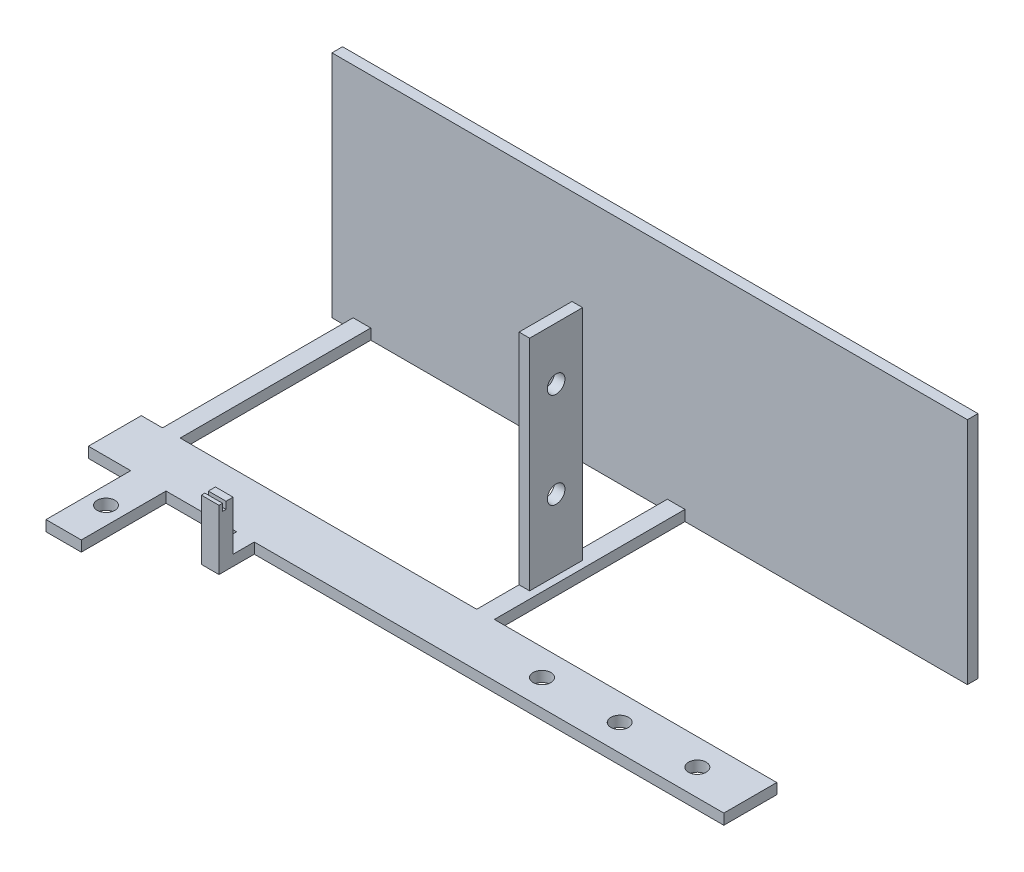
SolidWorks part; units mm, degrees
ref_plane "Front Plane" through (0, 0, 0) normal (0, 0, 1) x (1, 0, 0)
ref_plane "Top Plane" through (0, 0, 0) normal (0, 1, 0) x (1, 0, 0)
ref_plane "Right Plane" through (0, 0, 0) normal (1, 0, 0) x (0, 0, -1)
sketch "Sketch1" plane through (0, 0, 0) normal (0, 0, 1) x (1, 0, 0)
  line L1 (-900, 325) -> (900, 325)
  line L2 (-900, 325) -> (-900, -325)
  line L3 (-900, -325) -> (900, -325)
  line L4 (900, 325) -> (900, -325)
  line L5 (-900, 325) -> (900, -325) construction
  line L6 (-900, -325) -> (900, 325) construction
  point P0 (0, 0)
  dimension "D1" = 1800
  dimension "D2" = 650
extrude "Boss-Extrude1" add sketch "Sketch1" against normal blind 30
sketch "Sketch2" plane through (0, 0, 0) normal (0, 0, 1) x (1, 0, 0)
  line L0 (-900, -325) -> (900, -325) construction
  line L1 (100, -325) -> (50, -325)
  line L2 (100, -325) -> (100, -295)
  line L3 (100, -295) -> (50, -295)
  line L4 (50, -325) -> (50, -295)
  line L5 (900, -325) -> (900, 325) construction
  line L6 (-790, -325) -> (-840, -325)
  line L7 (-790, -325) -> (-790, -295)
  line L8 (-790, -295) -> (-840, -295)
  line L9 (-840, -325) -> (-840, -295)
  dimension "D1" = 30
  dimension "D2" = 50
  dimension "D3" = 50
  dimension "D4" = 30
  dimension "D5" = 800
  dimension "D6" = 840
extrude "Boss-Extrude2" add sketch "Sketch2" along normal blind 540
sketch "Sketch3" plane through (0, 0, 540) normal (0, 0, 1) x (1, 0, 0)
  line L0 (-900, 325) -> (-900, -325) construction
  line L1 (-900, -295) -> (900, -295)
  line L2 (-900, -295) -> (-900, -325)
  line L3 (-900, -325) -> (900, -325)
  line L4 (900, -295) -> (900, -325)
  dimension "D1" = 1800
  dimension "D2" = 30
extrude "Boss-Extrude4" add sketch "Sketch3" along normal blind 150
sketch "Sketch4" plane through (0, -295, 0) normal (0, 1, 0) x (1, 0, 0)
  line L0 (50, -540) -> (50, 0) construction
  line L1 (50, -420) -> (80, -420)
  line L2 (50, -420) -> (50, -270)
  line L3 (50, -270) -> (80, -270)
  line L4 (80, -420) -> (80, -270)
  line L5 (100, 0) -> (50, 0) construction
  line L6 (50, -540) -> (-790, -540) construction
  dimension "D1" = 150
  dimension "D2" = 30
  dimension "D3" = 270
  dimension "D4" = 120
extrude "Boss-Extrude5" add sketch "Sketch4" along normal blind 620
sketch "Sketch5" plane through (0, 0, 690) normal (0, 0, 1) x (1, 0, 0)
  line L0 (900, -295) -> (-900, -295) construction
  line L1 (-780, -295) -> (-680, -295)
  line L2 (-780, -295) -> (-780, -325)
  line L3 (-780, -325) -> (-680, -325)
  line L4 (-680, -295) -> (-680, -325)
  line L5 (-900, -325) -> (900, -325) construction
  line L6 (-900, -295) -> (-900, -325) construction
  dimension "D1" = 100
  dimension "D2" = 30
  dimension "D3" = 120
extrude "Boss-Extrude6" add sketch "Sketch5" along normal blind 240
sketch "Sketch6" plane through (0, 0, 690) normal (0, 0, 1) x (1, 0, 0)
  line L0 (900, -295) -> (-680, -295) construction
  line L1 (-480, -295) -> (-430, -295)
  line L2 (-480, -295) -> (-480, -325)
  line L3 (-480, -325) -> (-430, -325)
  line L4 (-430, -295) -> (-430, -325)
  line L5 (-680, -325) -> (900, -325) construction
  line L6 (-680, -325) -> (-680, -295) construction
  dimension "D1" = 30
  dimension "D2" = 50
  dimension "D3" = 200
extrude "Boss-Extrude7" add sketch "Sketch6" along normal blind 100
sketch "Sketch7" plane through (0, -295, 0) normal (0, 1, 0) x (1, 0, 0)
  line L0 (-480, -790) -> (-480, -690) construction
  line L1 (-430, -790) -> (-480, -790)
  line L2 (-430, -790) -> (-430, -750)
  line L3 (-430, -750) -> (-480, -750)
  line L4 (-480, -790) -> (-480, -750)
  dimension "D1" = 50
  dimension "D2" = 40
extrude "Boss-Extrude8" add sketch "Sketch7" along normal blind 140
sketch "Sketch8" plane through (0, -155, 0) normal (0, 1, 0) x (1, 0, 0)
  line L0 (-480, -750) -> (-480, -790) construction
  line L1 (-480, -780) -> (-430, -780)
  line L2 (-480, -780) -> (-480, -770)
  line L3 (-480, -770) -> (-430, -770)
  line L4 (-430, -780) -> (-430, -770)
  line L5 (-430, -790) -> (-430, -750) construction
  line L6 (-480, -790) -> (-430, -790) construction
  dimension "D1" = 10
  dimension "D2" = 10
extrude "Cut-Extrude1" cut sketch "Sketch8" against normal blind 20
sketch "Sketch9" plane through (0, -325, 0) normal (0, -1, 0) x (1, 0, 0)
  line L0 (-430, 690) -> (900, 690) construction
  line L1 (900, 690) -> (900, 540) construction
  circle A0 centre (750, 615) radius 25
  circle A1 centre (530, 615) radius 25
  circle A2 centre (310, 615) radius 25
  point P6 (0, 0)
  dimension "D1" = 50
  dimension "D2" = 75
  dimension "D3" = 150
  dimension "D4" = 220
  dimension "D5" = 220
extrude "Cut-Extrude2" cut sketch "Sketch9" against normal blind 40
sketch "Sketch10" plane through (50, 0, 0) normal (-1, 0, 0) x (0, 0, 1)
  line L0 (420, 325) -> (420, -295) construction
  line L1 (540, -295) -> (0, -295) construction
  circle A0 centre (345, -95) radius 25
  circle A1 centre (345, 175) radius 25
  point P8 (0, 0)
  point P9 (0, 0)
  dimension "D1" = 50
  dimension "D2" = 75
  dimension "D3" = 75
  dimension "D4" = 200
  dimension "D5" = 270
extrude "Cut-Extrude3" cut sketch "Sketch10" against normal blind 40
sketch "Sketch11" plane through (0, -325, 0) normal (0, -1, 0) x (1, 0, 0)
  line L0 (-680, 690) -> (-480, 690) construction
  line L1 (-680, 930) -> (-680, 690) construction
  circle A0 centre (-730, 810) radius 25
  dimension "D1" = 50
  dimension "D2" = 120
  dimension "D3" = 50
extrude "Cut-Extrude4" cut sketch "Sketch11" against normal blind 40
